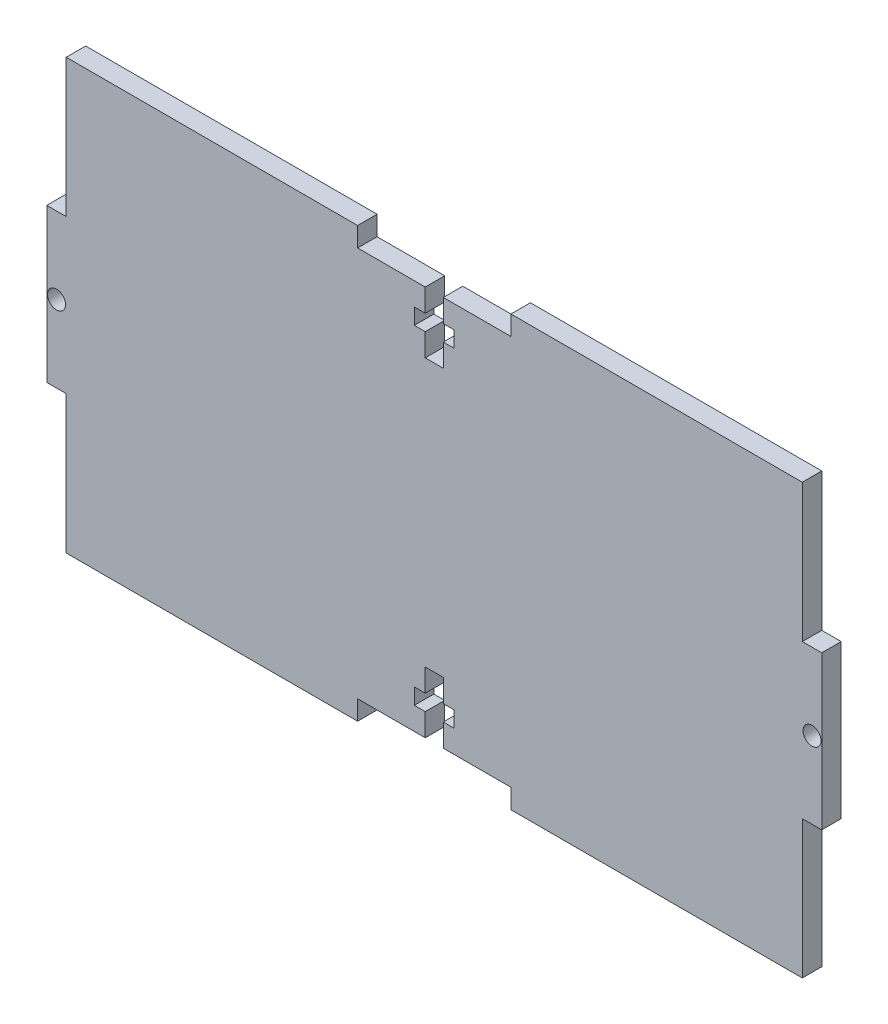
SolidWorks part; units mm, degrees
ref_plane "Front Plane" through (0, 0, 0) normal (0, 0, 1) x (1, 0, 0)
ref_plane "Top Plane" through (0, 0, 0) normal (0, 1, 0) x (1, 0, 0)
ref_plane "Right Plane" through (0, 0, 0) normal (1, 0, 0) x (0, 0, -1)
sketch "Sketch1" plane through (0, 0, 0) normal (0, 0, 1) x (1, 0, 0)
  line L0 (0, 35) -> (0, -35) construction
  line L1 (-60, 35) -> (60, 35)
  line L2 (-60, 35) -> (-60, -35)
  line L3 (-60, -35) -> (60, -35)
  line L4 (60, 35) -> (60, -35)
  line L5 (-60, 35) -> (60, -35) construction
  line L6 (-60, -35) -> (60, 35) construction
  line L7 (-60, 0) -> (60, 0) construction
  line L8 (-3.25, -25.525) -> (3.25, -25.525)
  line L9 (12.5, 35) -> (-12.5, 35)
  line L10 (12.5, 35) -> (12.5, 31.825)
  line L11 (12.5, 31.825) -> (-12.5, 31.825)
  line L12 (-12.5, 35) -> (-12.5, 31.825)
  line L13 (12.5, 35) -> (-12.5, 31.825) construction
  line L14 (12.5, 31.825) -> (-12.5, 35) construction
  line L15 (-1.47, 31.825) -> (1.47, 31.825)
  line L16 (-1.47, 31.825) -> (-1.47, 21.825)
  line L17 (-1.47, 21.825) -> (1.47, 21.825)
  line L18 (1.47, 31.825) -> (1.47, 21.825)
  line L19 (-1.47, 31.825) -> (1.47, 21.825) construction
  line L20 (-1.47, 21.825) -> (1.47, 31.825) construction
  line L21 (-3.25, 28.125) -> (3.25, 28.125)
  line L22 (-3.25, 28.125) -> (-3.25, 25.525)
  line L23 (-3.25, 25.525) -> (3.25, 25.525)
  line L24 (3.25, 28.125) -> (3.25, 25.525)
  line L25 (-3.25, 28.125) -> (3.25, 25.525) construction
  line L26 (-3.25, 25.525) -> (3.25, 28.125) construction
  line L27 (3.25, -28.125) -> (3.25, -25.525)
  line L28 (-3.25, -28.125) -> (3.25, -28.125)
  line L29 (-3.25, -28.125) -> (-3.25, -25.525)
  line L30 (-1.47, -21.825) -> (1.47, -21.825)
  line L31 (1.47, -31.825) -> (1.47, -21.825)
  line L32 (-1.47, -31.825) -> (1.47, -31.825)
  line L33 (-1.47, -31.825) -> (-1.47, -21.825)
  line L34 (12.5, -31.825) -> (-12.5, -31.825)
  line L35 (-12.5, -35) -> (-12.5, -31.825)
  line L36 (12.5, -35) -> (-12.5, -35)
  line L37 (12.5, -35) -> (12.5, -31.825)
  line L38 (63.175, -12.5) -> (60, -12.5)
  line L39 (-63.175, 12.5) -> (-60, 12.5)
  line L40 (-63.175, 12.5) -> (-63.175, -12.5)
  line L41 (-63.175, -12.5) -> (-60, -12.5)
  line L42 (-60, 12.5) -> (-60, -12.5)
  line L43 (-63.175, 12.5) -> (-60, -12.5) construction
  line L44 (-63.175, -12.5) -> (-60, 12.5) construction
  line L45 (60, 12.5) -> (60, -12.5)
  line L46 (63.175, 12.5) -> (60, 12.5)
  line L47 (63.175, 12.5) -> (63.175, -12.5)
  circle A0 centre (-61.5875, 0) radius 1.47
  circle A1 centre (61.5875, 0) radius 1.47
  point P0 (0, 0)
  point P10 (0, 33.4125)
  point P15 (0, 26.825)
  point P20 (0, 26.825)
  point P37 (-61.5875, 0)
  dimension "D11" = 2.94
  dimension "D1" = 70
  dimension "D2" = 120
  dimension "D3" = 3.175
  dimension "D4" = 10
  dimension "D5" = 2.94
  dimension "D6" = 25
  dimension "D7" = 6.5
  dimension "D8" = 2.6
  dimension "D9" = 6.3
  dimension "D10" = 3.175
extrude "Boss-Extrude1" add sketch "Sketch1" along normal mid plane 3.175 contours L21 L24 L23 L18 L17 L16 L22 L11 L12 L1 L2 L3 L4 L10 | L40 L39 L42 L41 | A0 | L38 L45 L46 L47 | A1
